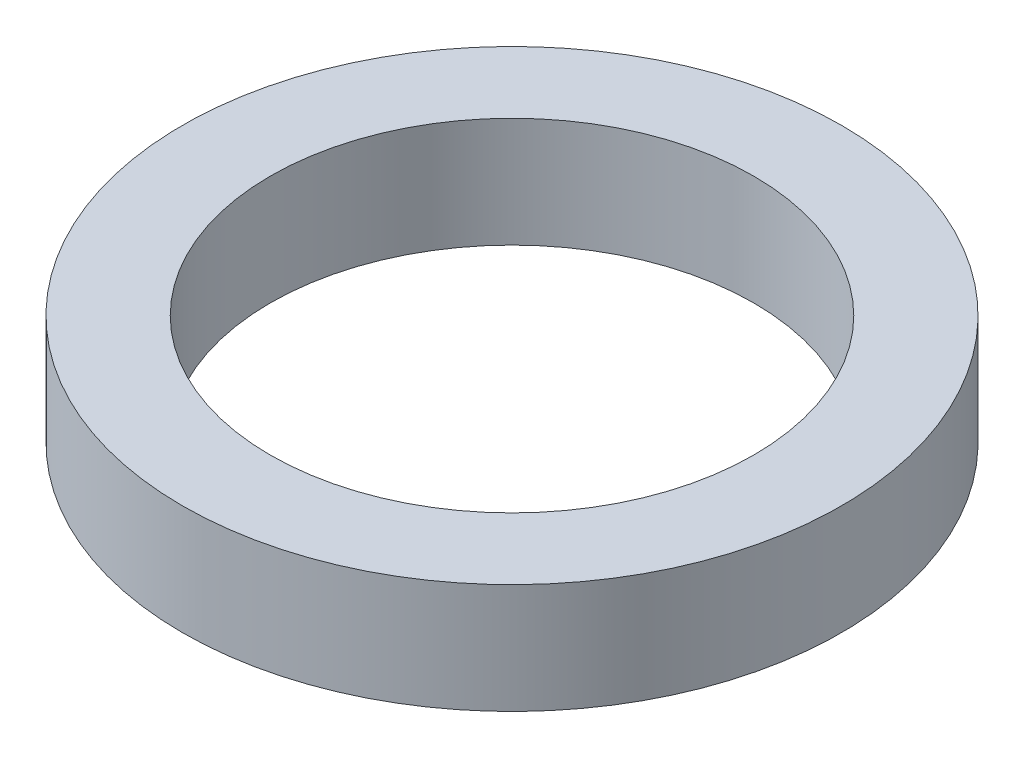
SolidWorks part; units mm, degrees
ref_plane "前视基准面" through (0, 0, 0) normal (0, 0, 1) x (1, 0, 0)
ref_plane "上视基准面" through (0, 0, 0) normal (0, 1, 0) x (1, 0, 0)
ref_plane "右视基准面" through (0, 0, 0) normal (1, 0, 0) x (0, 0, -1)
other "Configuration Table"
sketch "草图1" plane through (0, 0, 0) normal (0, 1, 0) x (1, 0, 0)
  circle A0 centre (0, 0) radius 11
  circle A1 centre (0, 0) radius 15
  dimension "D1" = 22
  dimension "D2" = 30
extrude "凸台-拉伸1" add sketch "草图1" along normal blind 5
